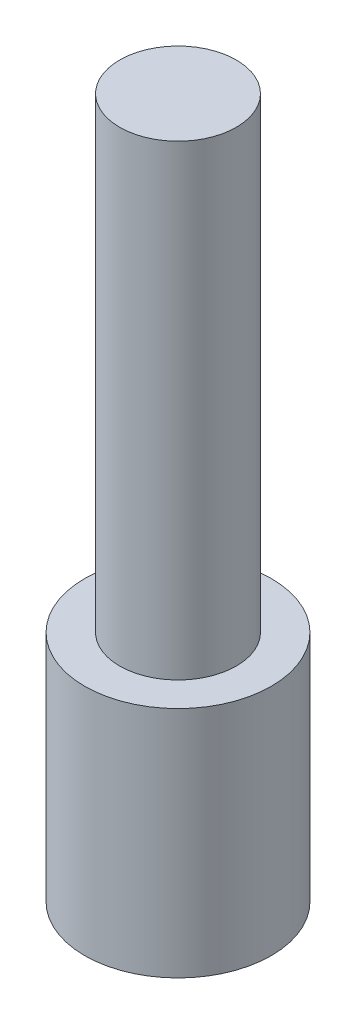
SolidWorks part; units mm, degrees
ref_plane "Front Plane" through (0, 0, 0) normal (0, 0, 1) x (1, 0, 0)
ref_plane "Top Plane" through (0, 0, 0) normal (0, 1, 0) x (1, 0, 0)
ref_plane "Right Plane" through (0, 0, 0) normal (1, 0, 0) x (0, 0, -1)
sketch "Sketch1" plane through (0, 0, 0) normal (0, 1, 0) x (1, 0, 0)
  circle A0 centre (0, 0) radius 2.5
  dimension "D1" = 5
extrude "Boss-Extrude1" add sketch "Sketch1" along normal blind 20
sketch "Sketch2" plane through (0, 0, 0) normal (0, -1, 0) x (1, 0, 0)
  circle A0 centre (0, 0) radius 4
  dimension "D1" = 8
extrude "Boss-Extrude2" add sketch "Sketch2" along normal blind 10
